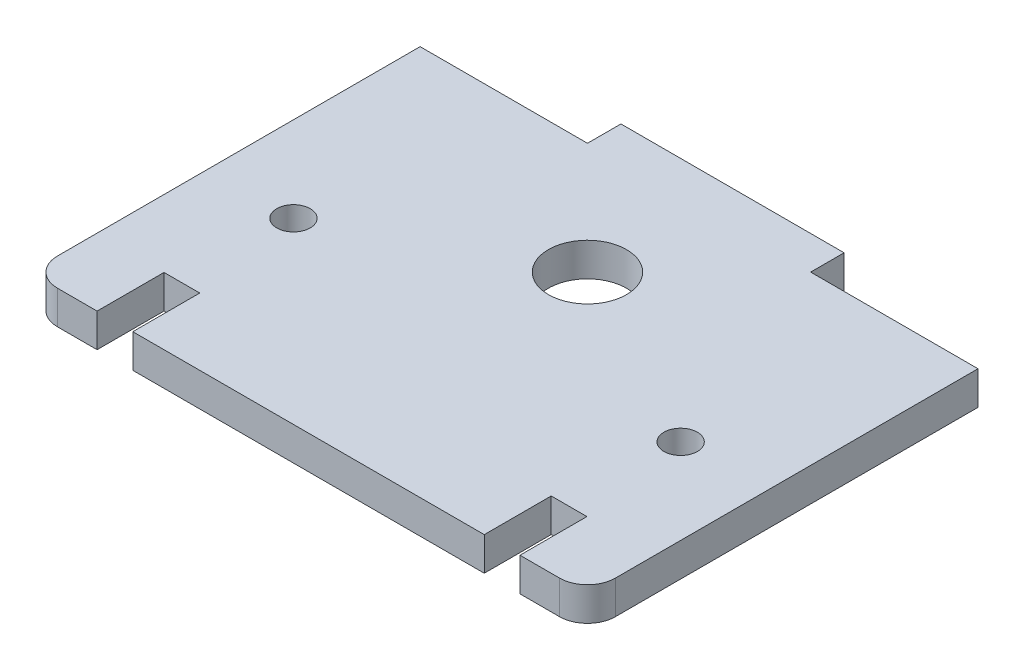
SolidWorks part; units mm, degrees
ref_plane "Alzado" through (0, 0, 0) normal (0, 0, 1) x (1, 0, 0)
ref_plane "Planta" through (0, 0, 0) normal (0, 1, 0) x (1, 0, 0)
ref_plane "Vista lateral" through (0, 0, 0) normal (1, 0, 0) x (0, 0, -1)
sketch "Croquis1" plane through (0, 0, 0) normal (0, 1, 0) x (1, 0, 0)
  line L0 (0, 0) -> (0, -17.5) construction
  line L1 (22.5, -17.5) -> (18.95, -17.5)
  line L2 (25, -15) -> (25, 17.5)
  line L3 (25, 17.5) -> (-25, 17.5)
  line L4 (-25, -15) -> (-25, 17.5)
  line L5 (25, -17.5) -> (-25, 17.5) construction
  line L6 (25, 17.5) -> (-25, -17.5) construction
  line L7 (-18.95, -17.5) -> (-18.95, -11.5)
  line L8 (-18.95, -11.5) -> (-15.75, -11.5)
  line L9 (-15.75, -11.5) -> (-15.75, -17.5)
  line L10 (-18.95, -17.5) -> (-22.5, -17.5)
  line L11 (18.95, -11.5) -> (15.75, -11.5)
  line L12 (18.95, -17.5) -> (18.95, -11.5)
  line L13 (15.75, -11.5) -> (15.75, -17.5)
  line L14 (15.75, -17.5) -> (-15.75, -17.5)
  circle A0 centre (-17.35, -1.5) radius 1.5
  circle A1 centre (17.35, -1.5) radius 1.5
  arc A2 (22.5, -17.5) -> (25, -15) centre (22.5, -15) ccw
  arc A3 (-22.5, -17.5) -> (-25, -15) centre (-22.5, -15) cw
  circle A4 centre (0, 7.5) radius 3.5
  point P0 (0, 0)
  point P15 (-17.35, -11.5)
  dimension "D6" = 3
  dimension "D8" = 2.5
  dimension "D10" = 7
  dimension "D1" = 50
  dimension "D2" = 35
  dimension "15.80" = 15.75
  dimension "D4" = 3.2
  dimension "D5" = 6
  dimension "D7" = 16
  dimension "D9" = 25
extrude "Saliente-Extruir1" add sketch "Croquis1" along normal blind 3
sketch "Croquis4" plane through (0, 0, -17.5) normal (0, 0, -1) x (-1, 0, 0)
  line L0 (0, 3) -> (0, 0) construction
  line L1 (-25, 3) -> (25, 3) construction
  line L2 (-10, -0.125) -> (-10, 3.125) construction
  line L3 (10, 0) -> (-10, 0)
  line L4 (10, 0) -> (10, 3)
  line L5 (10, 3) -> (-10, 3)
  line L6 (-10, 0) -> (-10, 3)
  line L7 (10, 0) -> (-10, 3) construction
  line L8 (10, 3) -> (-10, 0) construction
  point P5 (0, 1.5)
extrude "Saliente-Extruir2" add sketch "Croquis4" along normal blind 3
